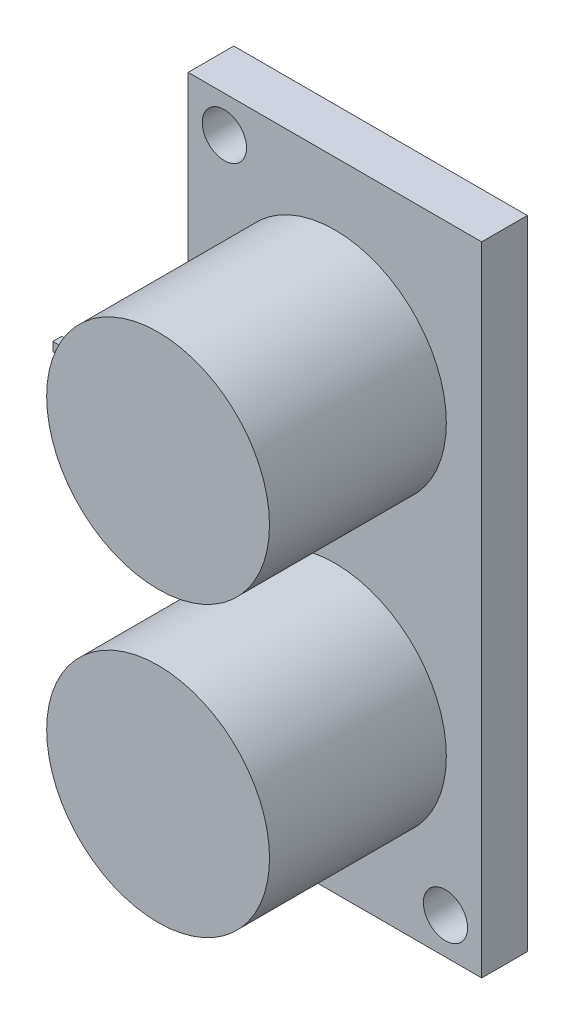
SolidWorks part; units mm, degrees
ref_plane "Front Plane" through (0, 0, 0) normal (1, 0, 0) x (0, 1, 0)
ref_plane "Top Plane" through (0, 0, 0) normal (0, 0, 1) x (0, 1, 0)
ref_plane "Right Plane" through (0, 0, 0) normal (0, 1, 0) x (-1, 0, 0)
sketch "Sketch1" plane through (0, 0, 0) normal (0, 0, 1) x (0, 1, 0)
  line L0 (-20.2882, -7.9375) -> (-22.8917, -7.9375) construction
  line L1 (-22.8918, 10.541) -> (22.8917, 10.541)
  line L2 (-22.8918, 10.541) -> (-22.8918, -10.541)
  line L3 (-22.8918, -10.541) -> (22.8917, -10.541)
  line L4 (22.8917, 10.541) -> (22.8917, -10.541)
  line L5 (-22.8918, 10.541) -> (22.8917, -10.541) construction
  line L6 (-22.8918, -10.541) -> (22.8917, 10.541) construction
  line L7 (-20.2882, -7.9375) -> (-20.2882, -10.541) construction
  line L8 (20.2883, 7.9375) -> (22.8917, 7.9375) construction
  line L9 (20.2883, 7.9375) -> (20.2882, 10.541) construction
  circle A0 centre (-20.2882, -7.9375) radius 1.5875
  circle A1 centre (20.2883, 7.9375) radius 1.5875
  point P0 (0, 0)
  dimension "D3" = 3.175
  dimension "D4" = 1.016
  dimension "D1" = 45.7835
  dimension "D2" = 21.082
  dimension "D5" = 2.6035
extrude "Boss-Extrude1" add sketch "Sketch1" along normal blind 3.2766
sketch "Sketch2" plane through (0, 0, 3.2766) normal (0, 0, 1) x (1, 0, 0)
  line L0 (0, 18.3635) -> (0, 22.8917) construction
  line L1 (10.541, 22.8917) -> (-10.541, 22.8917) construction
  line L2 (0, -18.3635) -> (0, -22.8918) construction
  line L3 (-10.541, -22.8918) -> (10.541, -22.8918) construction
  circle A0 centre (0, 10.3625) radius 8.001
  circle A1 centre (0, -10.3625) radius 8.001
  dimension "D1" = 16.002
  dimension "D2" = 4.5283
extrude "Boss-Extrude2" add sketch "Sketch2" along normal blind 12.7
sketch "Sketch3" plane through (0, 0, 3.2766) normal (0, 0, 1) x (1, 0, 0)
  line L1 (-12.319, 3.8417) -> (-9.779, 3.8417)
  line L2 (-12.319, 3.8417) -> (-12.319, -3.7783)
  line L3 (-12.319, -3.7783) -> (-9.779, -3.7783)
  line L4 (-9.779, 3.8417) -> (-9.779, -3.7783)
  line L5 (-12.319, 3.8417) -> (-9.779, -3.7783) construction
  line L6 (-12.319, -3.7783) -> (-9.779, 3.8417) construction
  line L7 (10.541, 22.8917) -> (-10.541, 22.8917) construction
  line L8 (-10.541, 22.8917) -> (-10.541, -22.8918) construction
  point P0 (-11.049, 0.0317)
  dimension "D1" = 7.62
  dimension "D2" = 2.54
  dimension "D3" = 19.05
  dimension "D4" = 0.762
extrude "Boss-Extrude3" add sketch "Sketch3" along normal blind 2.54
sketch "Sketch4" plane through (-12.319, 0, 0) normal (-1, 0, 0) x (0, -1, 0)
  line L0 (-3.8417, 4.5466) -> (3.7783, 4.5466) construction
  line L1 (-3.8417, 5.8166) -> (-3.8417, 3.2766) construction
  line L2 (3.7783, 5.8166) -> (3.7783, 3.2766) construction
  line L3 (-0.0317, 5.8166) -> (-0.0317, 3.2766) construction
  line L4 (-3.8417, 5.8166) -> (3.7783, 5.8166) construction
  line L5 (-3.8417, 3.2766) -> (3.7783, 3.2766) construction
  line L6 (2.8258, 4.8641) -> (2.8258, 4.2291)
  line L7 (-0.3492, 4.8641) -> (0.2858, 4.8641)
  line L8 (-0.3492, 4.8641) -> (-0.3492, 4.2291)
  line L9 (-0.3492, 4.2291) -> (0.2858, 4.2291)
  line L10 (0.2858, 4.8641) -> (0.2858, 4.2291)
  line L11 (-0.3492, 4.8641) -> (0.2858, 4.2291) construction
  line L12 (-0.3492, 4.2291) -> (0.2858, 4.8641) construction
  line L13 (-2.8892, 4.8641) -> (-2.2542, 4.8641)
  line L14 (-2.8892, 4.8641) -> (-2.8892, 4.2291)
  line L15 (-2.8892, 4.2291) -> (-2.2542, 4.2291)
  line L16 (-2.2542, 4.8641) -> (-2.2542, 4.2291)
  line L17 (-2.8892, 4.8641) -> (-2.2542, 4.2291) construction
  line L18 (-2.8892, 4.2291) -> (-2.2542, 4.8641) construction
  line L19 (2.8258, 4.2291) -> (2.1908, 4.2291)
  line L20 (2.1908, 4.8641) -> (2.1908, 4.2291)
  line L21 (2.8258, 4.8641) -> (2.1908, 4.8641)
  point P12 (-0.0317, 4.5466)
  point P17 (-2.5717, 4.5466)
  dimension "D1" = 0.635
  dimension "D2" = 1.905
extrude "Boss-Extrude4" add sketch "Sketch4" along normal blind 6.35
